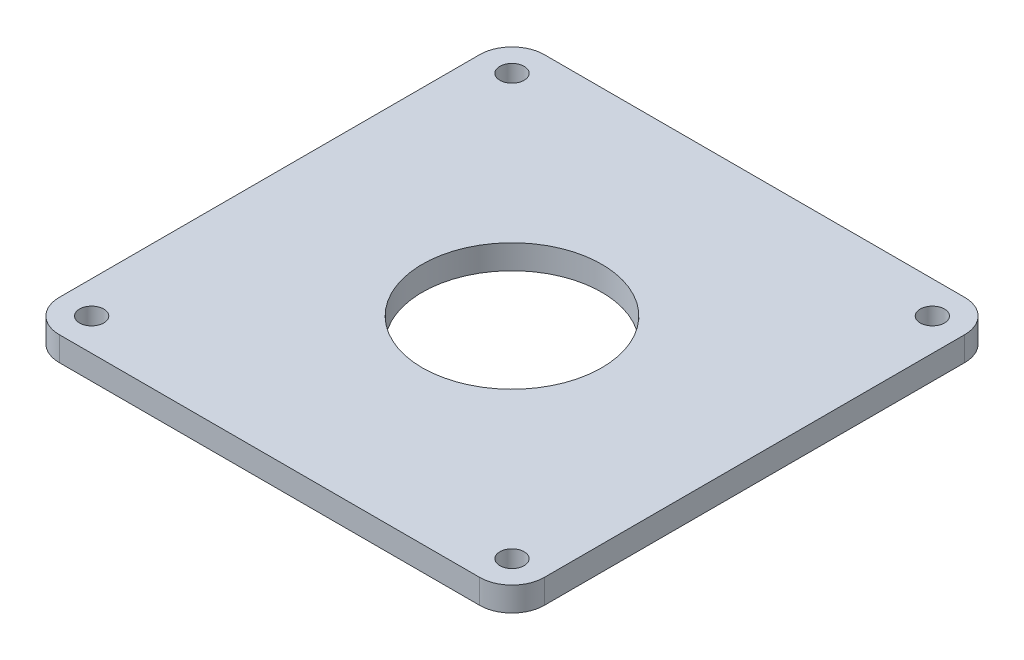
SolidWorks part; units mm, degrees
ref_plane "前视基准面" through (0, 0, 0) normal (0, 0, 1) x (1, 0, 0)
ref_plane "上视基准面" through (0, 0, 0) normal (0, 1, 0) x (1, 0, 0)
ref_plane "右视基准面" through (0, 0, 0) normal (1, 0, 0) x (0, 0, -1)
sketch "草图1" plane through (0, 0, 0) normal (0, 1, 0) x (1, 0, 0)
  line L1 (-26, -30) -> (26, -30)
  line L2 (-30, -26) -> (-30, 26)
  line L3 (-26, 30) -> (26, 30)
  line L4 (30, -26) -> (30, 26)
  line L7 (-26, -26) -> (26, -26) construction
  line L8 (-26, -26) -> (-26, 26) construction
  line L9 (-26, 26) -> (26, 26) construction
  line L10 (26, -26) -> (26, 26) construction
  circle A0 centre (-26, 26) radius 1.5
  circle A1 centre (26, 26) radius 1.5
  circle A2 centre (26, -26) radius 1.5
  circle A3 centre (-26, -26) radius 1.5
  arc A4 (-26, -30) -> (-30, -26) centre (-26, -26) cw
  arc A5 (26, -30) -> (30, -26) centre (26, -26) ccw
  arc A6 (26, 30) -> (30, 26) centre (26, 26) cw
  arc A7 (-30, 26) -> (-26, 30) centre (-26, 26) cw
  circle A8 centre (0, 0) radius 11.1
  point P0 (0, 0)
  point P5 (0, 0)
  point P14 (-30, -30)
  point P21 (0, 0)
  point P28 (-30, 30)
  dimension "D3" = 3
  dimension "D5" = 4
  dimension "D6" = 22.2
  dimension "D1" = 60
  dimension "D2" = 52
  dimension "D4" = 4
extrude "凸台-拉伸1" add sketch "草图1" along normal blind 3
